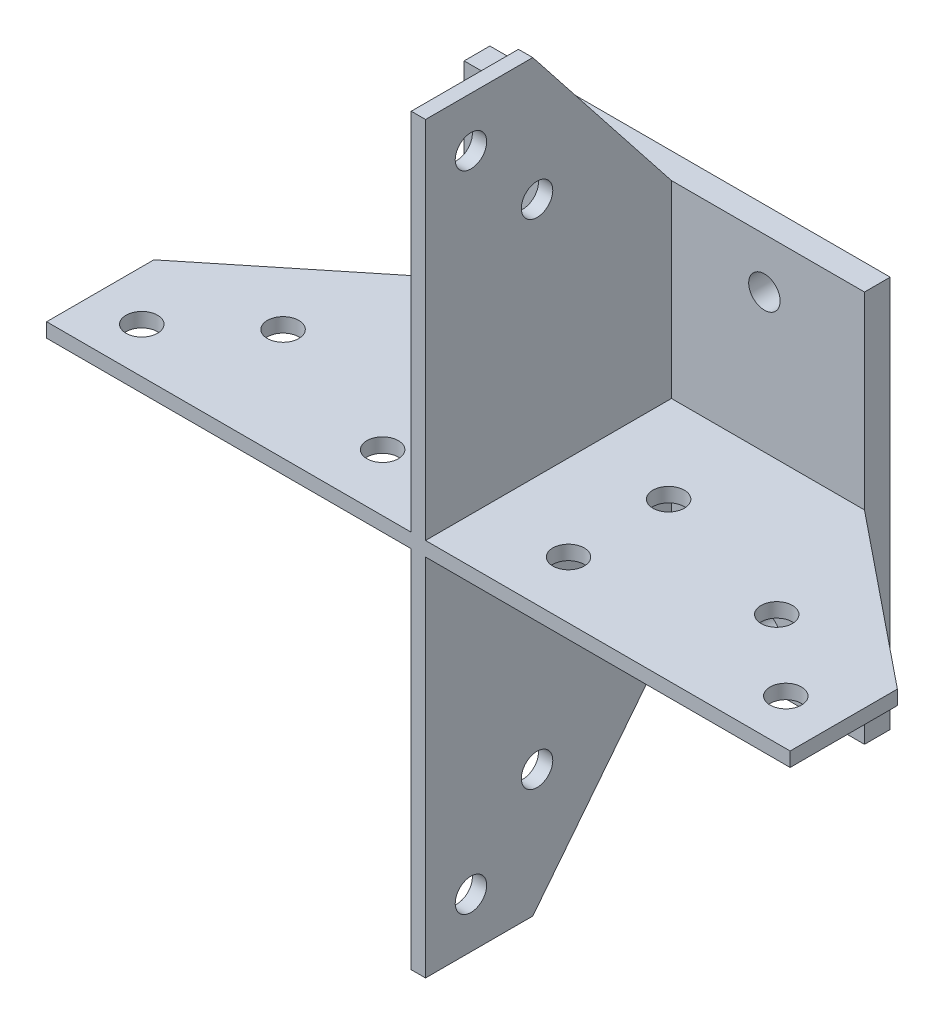
SolidWorks part; units mm, degrees
ref_plane "前视基准面" through (0, 0, 0) normal (0, 0, 1) x (1, 0, 0)
ref_plane "上视基准面" through (0, 0, 0) normal (0, 1, 0) x (1, 0, 0)
ref_plane "右视基准面" through (0, 0, 0) normal (1, 0, 0) x (0, 0, -1)
sketch "草图1" plane through (0, 0, 0) normal (0, 0, 1) x (1, 0, 0)
  line L1 (0, 0) -> (280, 0)
  line L2 (0, 0) -> (0, 274)
  line L3 (0, 274) -> (280, 274)
  line L4 (280, 0) -> (280, 274)
  dimension "D1" = 280
  dimension "D2" = 274
extrude "拉伸1" add sketch "草图1" along normal blind 18
sketch "草图2" plane through (0, 0, 18) normal (0, 0, 1) x (1, 0, 0)
  line L0 (140, -726) -> (140, 49274) construction
  line L1 (280, 0) -> (280, 274) construction
  line L2 (0, 0) -> (280, 0) construction
  line L3 (-120, 132) -> (400, 132)
  line L4 (-120, 132) -> (-120, 142)
  line L5 (-120, 142) -> (400, 142)
  line L6 (400, 132) -> (400, 142)
  dimension "D1" = 140
  dimension "D2" = 520
  dimension "D3" = 10
  dimension "D4" = 260
  dimension "D5" = 132
extrude "拉伸2" add sketch "草图2" along normal blind 172
sketch "草图3" plane through (0, 0, 18) normal (0, 0, 1) x (1, 0, 0)
  line L0 (-925.3527, 137) -> (49074.6473, 137) construction
  line L1 (280, 274) -> (0, 274) construction
  line L2 (280, 142) -> (280, 274) construction
  line L3 (135, 397) -> (145, 397)
  line L4 (135, 397) -> (135, -123)
  line L5 (135, -123) -> (145, -123)
  line L6 (145, 397) -> (145, -123)
  dimension "D1" = 137
  dimension "D2" = 520
  dimension "D3" = 10
  dimension "D4" = 260
  dimension "D5" = 135
extrude "拉伸3" add sketch "草图3" along normal blind 172
sketch "草图4" plane through (145, 0, 0) normal (1, 0, 0) x (0, 0, -1)
  line L0 (-115, 397) -> (-18, 274)
  line L1 (-190, 142) -> (-190, 397) construction
  line L2 (-115, 397) -> (-18, 397)
  line L3 (-18, 397) -> (-18, 274)
  dimension "D1" = 75
extrude "切除-拉伸1" cut sketch "草图4" against normal through all
sketch "草图5" plane through (135, 0, 0) normal (-1, 0, 0) x (0, 0, 1)
  line L0 (115, -123) -> (18, 0)
  line L1 (18, 0) -> (18, -123)
  line L2 (18, -123) -> (115, -123)
  line L3 (190, 132) -> (190, -123) construction
  dimension "D1" = 75
extrude "切除-拉伸2" cut sketch "草图5" against normal through all
sketch "草图6" plane through (0, 142, 0) normal (0, 1, 0) x (1, 0, 0)
  line L0 (280, -18) -> (400, -115)
  line L1 (400, -18) -> (280, -18)
  line L2 (400, -190) -> (145, -190) construction
  line L3 (400, -18) -> (400, -115)
  dimension "D1" = 75
extrude "切除-拉伸3" cut sketch "草图6" against normal through all
sketch "草图8" plane through (0, 142, 0) normal (0, 1, 0) x (1, 0, 0)
  line L0 (0, -18) -> (-120, -115)
  line L1 (-120, -115) -> (-120, -18)
  line L2 (-120, -18) -> (0, -18)
  line L3 (135, -190) -> (-120, -190) construction
  dimension "D1" = 75
extrude "切除-拉伸4" cut sketch "草图8" against normal through all
sketch "草图9" plane through (0, 132, 0) normal (0, -1, 0) x (1, 0, 0)
  line L0 (140, -796.0185) -> (140, 49203.9815) construction
  line L1 (-120, 190) -> (-120, 115) construction
  line L3 (0, 18) -> (135, 18) construction
  line L4 (145, 18) -> (280, 18) construction
  circle A0 centre (-85.1891, 158.2404) radius 11
  circle A1 centre (75, 150) radius 11
  circle A2 centre (-32.6366, 112) radius 11
  circle A3 centre (75, 80) radius 11
  circle A4 centre (205, 150) radius 11
  circle A5 centre (205, 80) radius 11
  circle A6 centre (365.1891, 158.2404) radius 11
  circle A7 centre (312.6366, 112) radius 11
  dimension "D1" = 260
  dimension "D6" = 52.5525
  dimension "D2" = 65
  dimension "D3" = 65
  dimension "D4" = 172.6366
  dimension "D5" = 172.6366
  dimension "D7" = 52.5525
  dimension "D8" = 62
  dimension "D9" = 70
  dimension "D10" = 94
  dimension "D11" = 69.9996
extrude "切除-拉伸5" cut sketch "草图9" against normal through all
sketch "草图10" plane through (145, 0, 0) normal (1, 0, 0) x (0, 0, -1)
  line L0 (-1158.0474, 137) -> (48841.9526, 137) construction
  line L1 (-190, 397) -> (-115, 397) construction
  line L2 (-18, 142) -> (-18, 274) construction
  circle A0 centre (-158.2411, 362.1891) radius 11
  circle A1 centre (-112, 309.6366) radius 11
  circle A2 centre (-112, -35.6366) radius 11
  circle A3 centre (-158.2411, -88.1891) radius 11
  dimension "D2" = 172.6366
  dimension "D1" = 260
  dimension "D3" = 172.6366
  dimension "D4" = 52.5525
  dimension "D5" = 52.5525
  dimension "D6" = 94
  dimension "D7" = 70
extrude "切除-拉伸6" cut sketch "草图10" against normal through all
sketch "草图11" plane through (0, 0, 0) normal (0, 0, -1) x (-1, 0, 0)
  line L0 (0, 0) -> (-280, 0) construction
  line L1 (-280, 0) -> (-280, 274) construction
  circle A0 centre (-210, 35) radius 11
  point P2 (-140, 0)
  point P5 (-280, 137)
  dimension "D1" = 70
  dimension "D2" = 102
extrude "切除-拉伸7" cut sketch "草图11" against normal through all
pattern_linear "阵列(线性)1" count 2 spacing 140 along (-1, 0, 0) count 2 spacing 204 along (0, 1, 0) of "切除-拉伸7"
